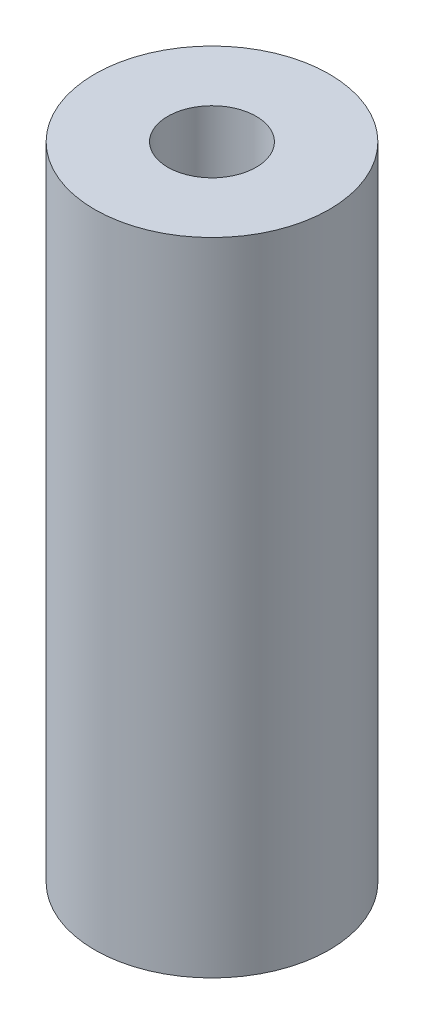
SolidWorks part; units mm, degrees
material "1060 Alloy"
ref_plane "Front Plane" through (0, 0, 0) normal (0, 0, 1) x (1, 0, 0)
ref_plane "Top Plane" through (0, 0, 0) normal (0, 1, 0) x (1, 0, 0)
ref_plane "Right Plane" through (0, 0, 0) normal (1, 0, 0) x (0, 0, -1)
sketch "Sketch1" plane through (0, 0, 0) normal (0, 1, 0) x (1, 0, 0)
  circle A0 centre (0, 0) radius 3
  dimension "D1" = 6
extrude "Boss-Extrude1" add sketch "Sketch1" along normal blind 16.4
hole_wizard "#4-40 Tapped Hole1" positions "Sketch2" profile "Sketch3" tap size "#4-40" standard "ANSI Inch" end condition through all
sketch "Sketch2" plane through (0, 16.4, 0) normal (0, 1, 0) x (1, 0, 0)
  point P0 (0, 0)
sketch "Sketch3" plane through (0, 16.4, 0) normal (1, 0, 0) x (0, 0, 1)
  line L0 (0, 0) -> (0, 16.4)
  line L1 (0, 16.4) -> (1.1303, 16.4)
  line L2 (1.1303, 16.4) -> (1.1303, 0)
  line L5 (1.1303, 0) -> (0, 0)
  line L11 (0, -6.35) -> (0, 107.95) construction
  dimension "Thru Tap Drill Dia." = 2.2606
  dimension "Thru Tap Drill Depth" = 16.4
cosmetic thread "Hole Thread1"
